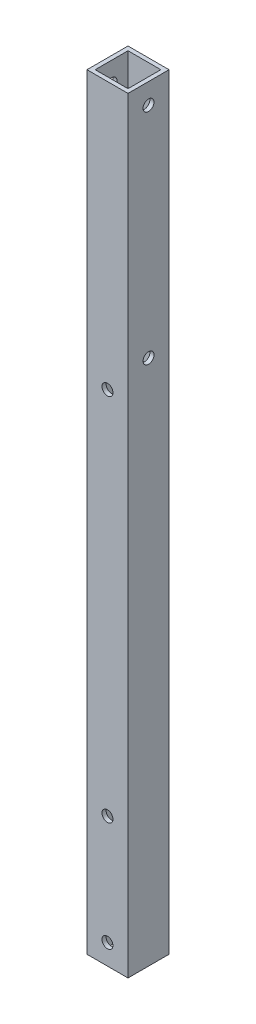
SolidWorks part; units mm, degrees
material "1060 合金"
ref_plane "正面" through (0, 0, 0) normal (0, 0, 1) x (1, 0, 0)
ref_plane "平面" through (0, 0, 0) normal (0, 1, 0) x (1, 0, 0)
ref_plane "右側面" through (0, 0, 0) normal (1, 0, 0) x (0, 0, -1)
sketch "ｽｹｯﾁ1" plane through (0, 0, 0) normal (0, 1, 0) x (1, 0, 0)
  line L1 (-7.5, -7.5) -> (7.5, -7.5)
  line L2 (-7.5, -7.5) -> (-7.5, 7.5)
  line L3 (-7.5, 7.5) -> (7.5, 7.5)
  line L4 (7.5, -7.5) -> (7.5, 7.5)
  line L5 (-7.5, -7.5) -> (7.5, 7.5) construction
  line L6 (-7.5, 7.5) -> (7.5, -7.5) construction
  point P0 (0, 0)
  dimension "D1" = 15
extrude "押し出し-薄板1" add sketch "ｽｹｯﾁ1" along normal blind 280 thin thin type one direction reverse wall 1.5
sketch "ｽｹｯﾁ2" plane through (7.5, 0, 0) normal (1, 0, 0) x (0, 0, -1)
  line L0 (0, 0) -> (0, 280) construction
  line L1 (-7.5, 280) -> (7.5, 280) construction
  circle A0 centre (0, 272.5) radius 2
  circle A1 centre (0, 192.5) radius 2
  dimension "D1" = 7.5
  dimension "D2" = 80
  dimension "D3" = 4
extrude "ｶｯﾄ - 押し出し1" cut sketch "ｽｹｯﾁ2" against normal through all
sketch "ｽｹｯﾁ3" plane through (0, 0, 7.5) normal (0, 0, 1) x (1, 0, 0)
  line L0 (0, 0) -> (0, 280) construction
  line L1 (-7.5, 280) -> (7.5, 280) construction
  line L2 (-7.5, 0) -> (7.5, 0) construction
  circle A0 centre (0, 7.5) radius 2
  circle A1 centre (0, 47.5) radius 2
  circle A3 centre (0, 182.5) radius 2
  dimension "D1" = 7.5
  dimension "D2" = 40
  dimension "D3" = 4
  dimension "D5" = 97.5
  dimension "D6" = 4
extrude "ｶｯﾄ - 押し出し2" cut sketch "ｽｹｯﾁ3" against normal through all
